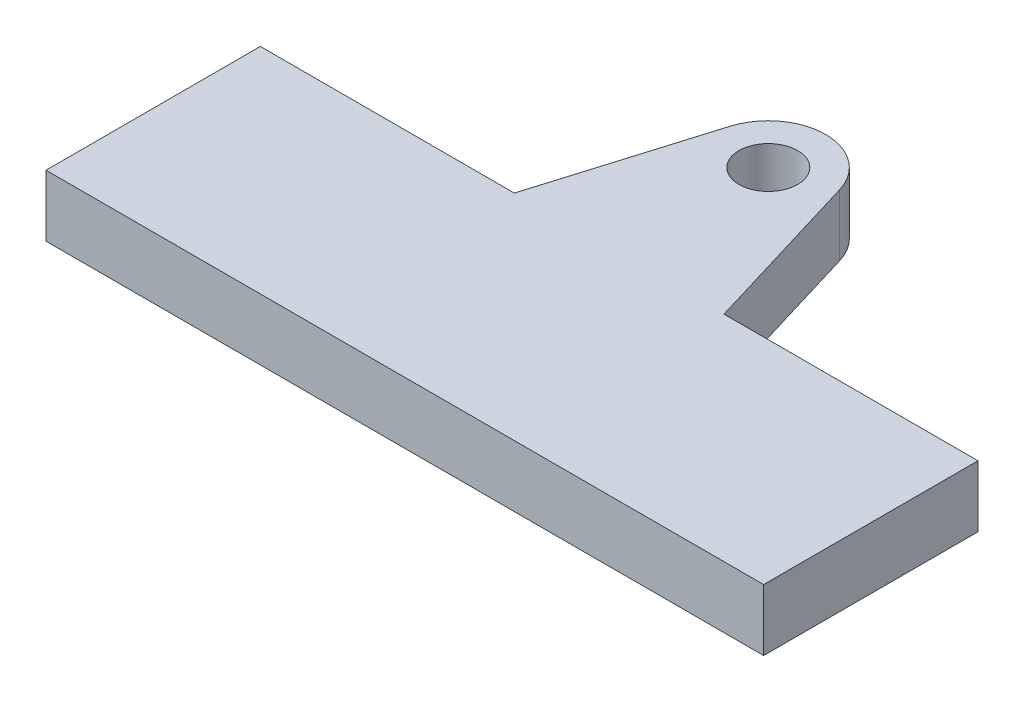
SolidWorks part; units mm, degrees
ref_plane "前视基准面" through (0, 0, 0) normal (0, 0, 1) x (1, 0, 0)
ref_plane "上视基准面" through (0, 0, 0) normal (0, 1, 0) x (1, 0, 0)
ref_plane "右视基准面" through (0, 0, 0) normal (1, 0, 0) x (0, 0, -1)
sketch "草图1" plane through (0, 0, 0) normal (0, 1, 0) x (1, 0, 0)
  line L0 (-11.2496, 0) -> (-5.888, 17.7759)
  line L1 (-38.5, 0) -> (38.5, 0)
  line L2 (-38.5, 0) -> (-38.5, -23)
  line L3 (-38.5, -23) -> (38.5, -23)
  line L4 (38.5, 0) -> (38.5, -23)
  line L5 (5.888, 17.7759) -> (11.2496, 0)
  circle A0 centre (0, 16) radius 3.15
  arc A1 (-5.888, 17.7759) -> (5.888, 17.7759) centre (0, 16) cw
  point P4 (0, 0)
  point P12 (0, 0)
  dimension "D3" = 6.3
  dimension "D5" = 3
  dimension "D1" = 77
  dimension "D2" = 23
  dimension "D4" = 16
extrude "凸台-拉伸1" add sketch "草图1" along normal blind 6.6 contours A1 L0 L1 L5 A0 | L4 L1 L2 L3
